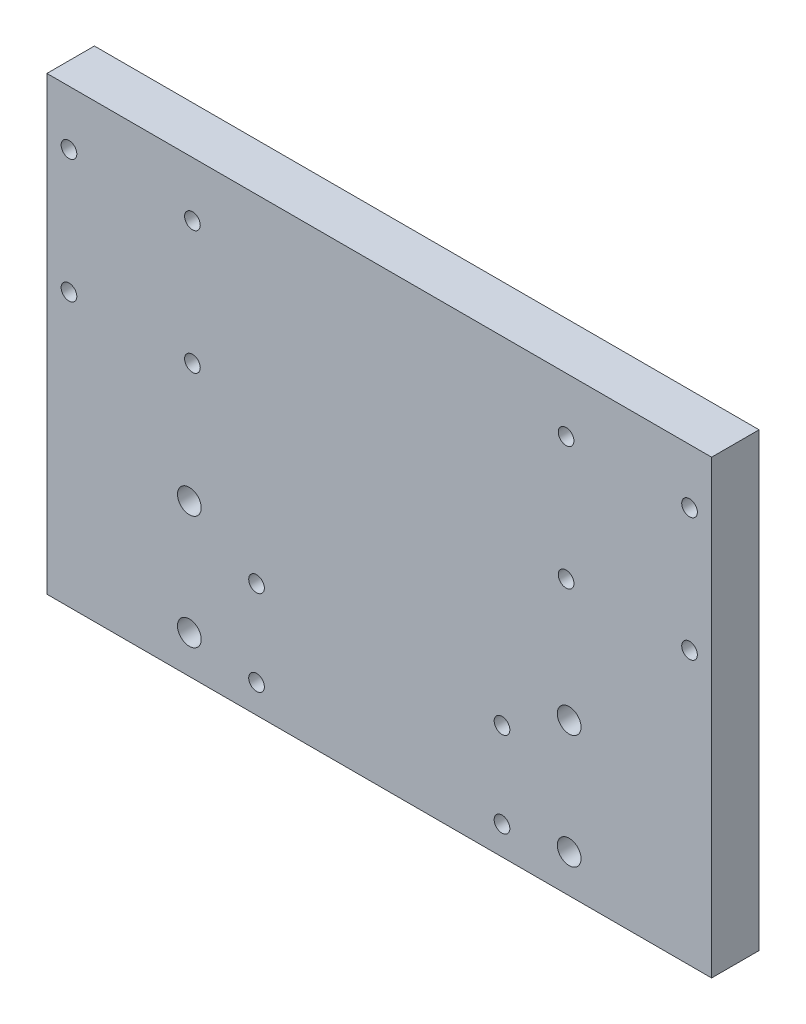
SolidWorks part; units mm, degrees
ref_plane "前视基准面" through (0, 0, 0) normal (0, 0, 1) x (1, 0, 0)
ref_plane "上视基准面" through (0, 0, 0) normal (0, 1, 0) x (1, 0, 0)
ref_plane "右视基准面" through (0, 0, 0) normal (1, 0, 0) x (0, 0, -1)
other "Configuration Table"
sketch "草图1" plane through (0, 0, 0) normal (0, 0, 1) x (1, 0, 0)
  line L1 (0, 0) -> (140, 0)
  line L2 (0, 0) -> (0, 95)
  line L3 (0, 95) -> (140, 95)
  line L4 (140, 0) -> (140, 95)
  dimension "D1" = 140
  dimension "D2" = 95
extrude "凸台-拉伸1" add sketch "草图1" along normal blind 10
sketch "草图2" plane through (0, 0, 10) normal (0, 0, 1) x (1, 0, 0)
  line L0 (70, 95) -> (70, -6.2797) construction
  line L1 (140, 95) -> (0, 95) construction
  circle A0 centre (4.65, 83.45) radius 1.621
  circle A1 centre (30.65, 83.45) radius 1.621
  circle A2 centre (30.65, 57.45) radius 1.621
  circle A3 centre (4.65, 57.45) radius 1.621
  circle A4 centre (30, 32) radius 3.25
  circle A5 centre (30, 8) radius 3.25
  circle A6 centre (44.15, 6) radius 1.65
  circle A7 centre (44.15, 24) radius 1.65
  circle A8 centre (95.85, 24) radius 1.65
  circle A9 centre (95.85, 6) radius 1.65
  circle A10 centre (110, 8) radius 3.25
  circle A11 centre (110, 32) radius 3.25
  circle A12 centre (135.35, 57.45) radius 1.621
  circle A13 centre (109.35, 57.45) radius 1.621
  circle A14 centre (109.35, 83.45) radius 1.621
  circle A15 centre (135.35, 83.45) radius 1.621
hole_wizard "M4 螺纹孔1" positions "3D草图1" profile "草图4" tap size "M4" standard "GB" end condition through all
sketch3d "3D草图1"
  point P0 (4.65, 83.45, 10)
  point P3 (4.65, 57.45, 10)
  point P6 (30.65, 57.45, 10)
  point P9 (30.65, 83.45, 10)
  point P12 (109.35, 83.45, 10)
  point P15 (135.35, 83.45, 10)
  point P18 (135.35, 57.45, 10)
  point P21 (109.35, 57.45, 10)
  point P24 (44.15, 24, 10)
  point P27 (44.15, 6, 10)
  point P30 (95.85, 24, 10)
  point P33 (95.85, 6, 10)
sketch "草图4" plane through (4.65, 83.45, 10) normal (1, 0, 0) x (0, -1, 0)
  line L0 (0, 0) -> (0, 10)
  line L1 (0, 10) -> (1.65, 10)
  line L2 (1.65, 10) -> (1.65, 0)
  line L5 (1.65, 0) -> (0, 0)
  line L11 (0, -6.35) -> (0, 107.95) construction
  dimension "通孔螺纹孔钻头直径" = 3.3
  dimension "通孔螺纹孔钻头深度" = 10
cosmetic thread "孔螺蚊线1" parameters "D2"=4
cosmetic thread "孔螺蚊线2" parameters "D2"=4
cosmetic thread "孔螺蚊线3" parameters "D2"=4
cosmetic thread "孔螺蚊线4" parameters "D2"=4
cosmetic thread "孔螺蚊线5" parameters "D2"=4
cosmetic thread "孔螺蚊线6" parameters "D2"=4
cosmetic thread "孔螺蚊线7" parameters "D2"=4
cosmetic thread "孔螺蚊线8" parameters "D2"=4
cosmetic thread "孔螺蚊线9" parameters "D2"=4
cosmetic thread "孔螺蚊线10" parameters "D2"=4
cosmetic thread "孔螺蚊线11" parameters "D2"=4
cosmetic thread "孔螺蚊线12" parameters "D2"=4
hole_wizard "M6 螺纹孔1" positions "3D草图2" profile "草图5" tap size "M6" standard "GB" end condition through all
sketch3d "3D草图2"
  point P0 (30, 32, 10)
  point P3 (30, 8, 10)
  point P6 (110, 32, 10)
  point P9 (110, 8, 10)
sketch "草图5" plane through (30, 32, 10) normal (1, 0, 0) x (0, -1, 0)
  line L0 (0, 0) -> (0, 10)
  line L1 (0, 10) -> (2.5, 10)
  line L2 (2.5, 10) -> (2.5, 0)
  line L5 (2.5, 0) -> (0, 0)
  line L11 (0, -6.35) -> (0, 107.95) construction
  dimension "通孔螺纹孔钻头直径" = 5
  dimension "通孔螺纹孔钻头深度" = 10
cosmetic thread "孔螺蚊线13" parameters "D2"=6
cosmetic thread "孔螺蚊线14" parameters "D2"=6
cosmetic thread "孔螺蚊线15" parameters "D2"=6
cosmetic thread "孔螺蚊线16" parameters "D2"=6
